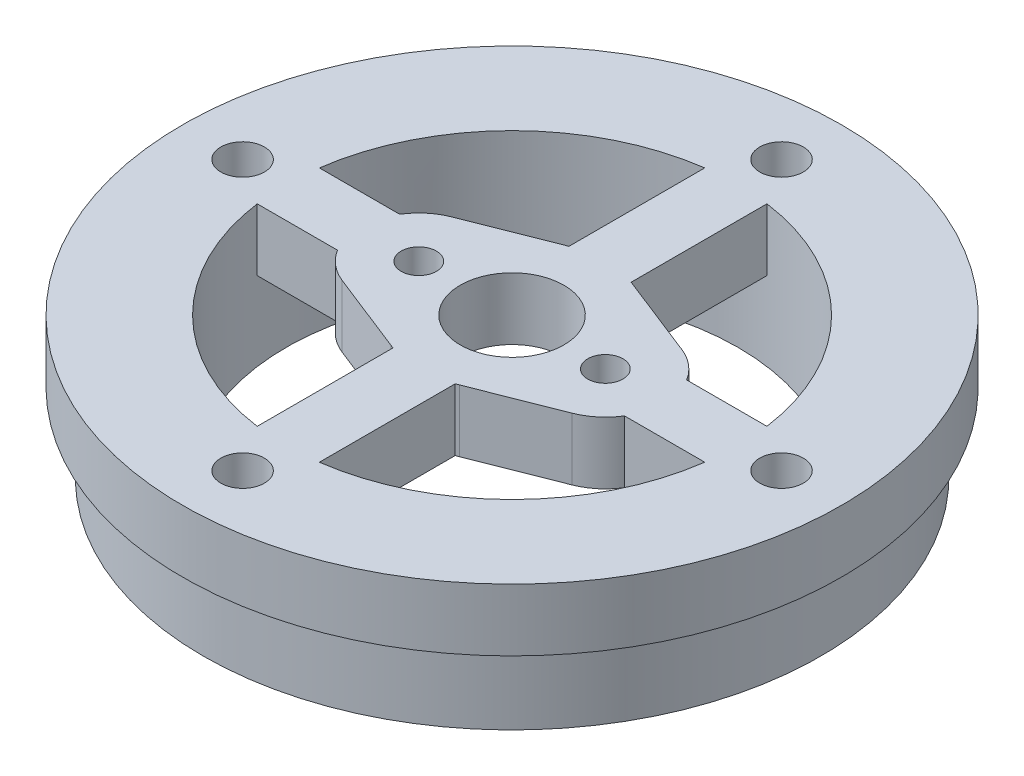
SolidWorks part; units mm, degrees
ref_plane "前视基准面" through (0, 0, 0) normal (0, 0, 1) x (1, 0, 0)
ref_plane "上视基准面" through (0, 0, 0) normal (0, 1, 0) x (1, 0, 0)
ref_plane "右视基准面" through (0, 0, 0) normal (1, 0, 0) x (0, 0, -1)
sketch "草图2" plane through (0, 0, 0) normal (0, 0, 1) x (1, 0, 0)
  line L0 (0, 0) -> (0, 5.9817) construction
  line L1 (2.5, 6.8) -> (15.9, 6.8)
  line L2 (15.9, 6.8) -> (15.9, 3.8)
  line L3 (15.9, 3.8) -> (14.9, 3.8)
  line L4 (14.9, 3.8) -> (14.9, 0)
  line L5 (14.9, 0) -> (10.9, 0)
  line L6 (10.9, 0) -> (10.9, 3.8)
  line L7 (10.9, 3.8) -> (2.5, 3.8)
  line L9 (2.5, 3.8) -> (2.5, 6.8)
  dimension "D1" = 3.8
  dimension "D2" = 29.8
  dimension "D3" = 4
  dimension "D4" = 3
  dimension "D5" = 1
  dimension "D6" = 2.5
revolve "旋转1" add sketch "草图2" angle 360 about L0
hole_wizard "Ø1.7 (1.7) 直径孔1" positions "草图3" profile "草图4" hole size "Ø1.7" standard "GB"
sketch "草图3" plane through (0, 6.8, 0) normal (0, 1, 0) x (1, 0, 0)
  line L0 (0, 0) -> (1.6536, 0) construction
  line L2 (0, 0) -> (0, 4.5257) construction
  point P11 (4.5, 0)
  point P17 (-4.5, 0)
  dimension "D1" = 9
sketch "草图4" plane through (-4.5, 6.8, 0) normal (1, 0, 0) x (0, 0, 1)
  line L0 (0, 0) -> (0, 6)
  line L1 (0, 6) -> (0.85, 6)
  line L2 (0.85, 6) -> (0.85, 0)
  line L5 (0.85, 0) -> (0, 0)
  line L10 (0, 6) -> (-0.85, 6) construction
  line L11 (0, -6.35) -> (0, 107.95) construction
  dimension "孔直径" = 1.7
  dimension "孔深度" = 6
  dimension "导头角度" = 180
hole_wizard "Ø2.1 (2.1) 直径孔1" positions "草图7" profile "草图8" hole size "Ø2.1" standard "GB" end condition through all
sketch "草图7" plane through (0, 0, 0) normal (0, -1, 0) x (-1, 0, 0)
  line L1 (0, 0) -> (-13, 0) construction
  point P11 (-13, 0)
  point P17 (0, 13)
  point P18 (13, 0)
  point P19 (0, -13)
  dimension "D2" = 13
  dimension "D1" = 4
sketch "草图8" plane through (13, 0, 0) normal (1, 0, 0) x (0, 0, -1)
  line L0 (0, 0) -> (0, 6.8)
  line L1 (0, 6.8) -> (1.05, 6.8)
  line L2 (1.05, 6.8) -> (1.05, 0)
  line L5 (1.05, 0) -> (0, 0)
  line L11 (0, -6.35) -> (0, 107.95) construction
  dimension "通孔孔直径" = 2.1
  dimension "通孔孔深度" = 6.8
sketch "草图9" plane through (0, 3.8, 0) normal (0, -1, 0) x (1, 0, 0)
  line L0 (-1.65, 4.1866) -> (-5.545, 2.6515)
  line L1 (-5.545, -2.6515) -> (-1.65, -4.1866)
  line L2 (1.65, 4.1866) -> (5.545, 2.6515)
  line L3 (5.545, -2.6515) -> (1.65, -4.1866)
  line L4 (-6.9233, 1.5) -> (-10.7963, 1.5)
  line L5 (0, 0) -> (-18.3876, 0) construction
  line L6 (-6.9233, -1.5) -> (-10.7963, -1.5)
  line L7 (0, 0) -> (0, 17.2445) construction
  line L8 (-1.5, 4.2426) -> (-1.5, 10.7963)
  line L9 (1.5, 4.2426) -> (1.5, 10.7963)
  line L10 (6.9233, -1.5) -> (10.7963, -1.5)
  line L11 (6.9233, 1.5) -> (10.7963, 1.5)
  line L12 (1.5, -4.2426) -> (1.5, -10.7963)
  line L13 (-1.5, -4.2426) -> (-1.5, -10.7963)
  circle A2 centre (0, 0) radius 10.9 construction
  circle A3 centre (0, 0) radius 10.9
  circle A8 centre (-4.5, 0) radius 2.85
  arc A9 (-5.545, 2.6515) -> (-5.545, -2.6515) centre (-4.5, 0) ccw
  circle A11 centre (4.5, 0) radius 2.85
  arc A12 (5.545, -2.6515) -> (5.545, 2.6515) centre (4.5, 0) ccw
  arc A13 (1.65, 4.1866) -> (-1.65, 4.1866) centre (0, 0) ccw
  circle A14 centre (0, 0) radius 4.5
  arc A15 (-1.65, -4.1866) -> (1.65, -4.1866) centre (0, 0) ccw
  circle M22 centre (0, 0) radius 10.9
  dimension "D1" = 2
  dimension "D4" = 3
  dimension "D5" = 3
  dimension "D2" = 2
  dimension "D3" = 2
extrude "切除-拉伸1" cut sketch "草图9" against normal blind 10 contours A13 L8 L4 A9 L0 M22 | A15 L1 A9 L6 L13 M22 | A13 L2 A12 L11 L9 M22 | A15 L12 L10 A12 L3 M22
